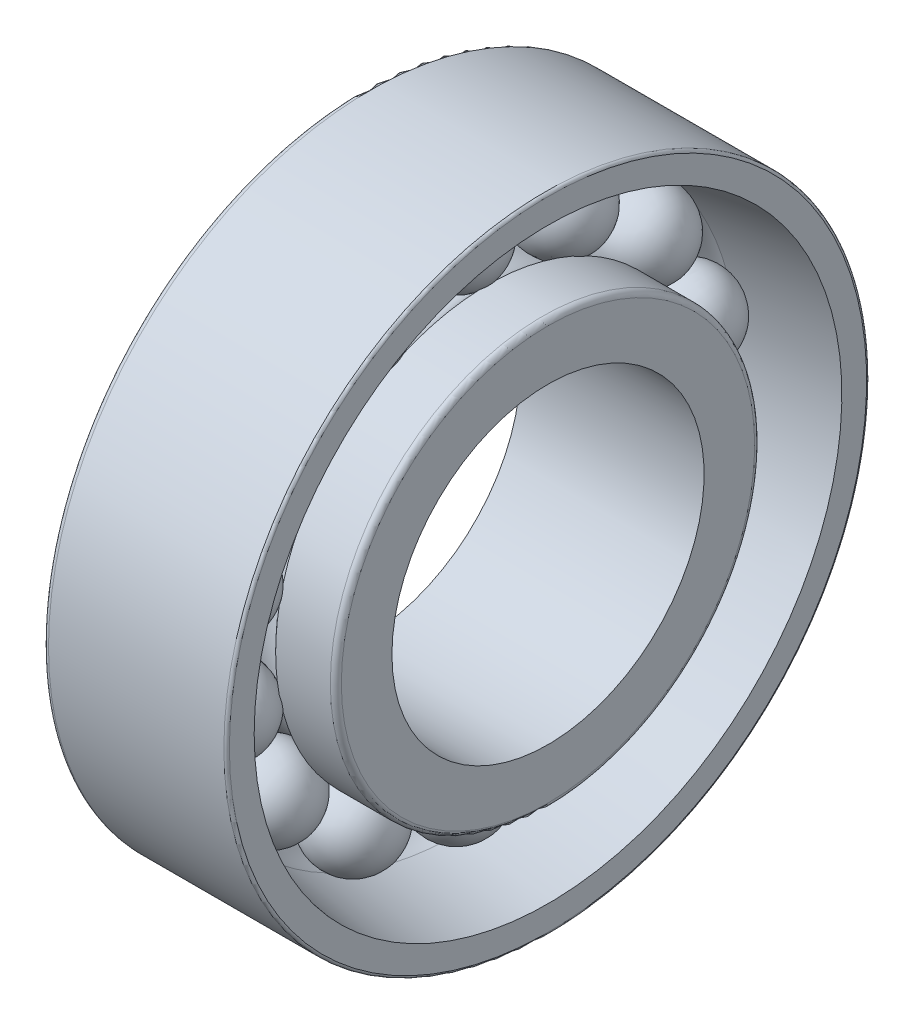
SolidWorks part; units mm, degrees
material "GCr15"
ref_plane "前视" through (0, 0, 0) normal (0, 0, 1) x (1, 0, 0)
ref_plane "上视" through (0, 0, 0) normal (0, 1, 0) x (1, 0, 0)
ref_plane "右视" through (0, 0, 0) normal (1, 0, 0) x (0, 0, -1)
sketch "尺寸草图" plane through (0, 0, 0) normal (0, 0, 1) x (1, 0, 0)
  line L0 (-3.205, -4.1476) -> (31.795, -4.1476)
  point P2 (13.795, -4.1476)
  point P3 (3.795, -4.1476)
  point P4 (0.7517, -4.1476)
  point P7 (31.645, -4.1476)
  point P8 (31.495, -4.1476)
  dimension "DD" = 35
  dimension "d" = 17
  dimension "B" = 10
  dimension "r1" = 0.15
  dimension "r" = 0.3
sketch "草图1" plane through (0, 0, 0) normal (0, 0, 1) x (1, 0, 0)
  line L0 (0, 0) -> (106.1418, 0) construction
  line L1 (0, 0) -> (0, 122.9209) construction
  line L2 (0, 17.5) -> (10, 17.5)
  line L3 (0, 8.5) -> (10, 8.5)
  line L4 (0, 17.5) -> (0, 8.5)
  line L5 (10, 17.5) -> (10, 11.5537)
  line L6 (10, 8.5) -> (10, 11.5537)
  line L7 (10, 11.5537) -> (0, 11.5537)
  line L9 (0, 13) -> (95.9613, 13) construction
  line L10 (5, 0) -> (5, 122.9209) construction
  line L11 (5, 15.25) -> (9, 15.25)
  line L12 (3.2764, 14.4463) -> (0, 14.4463)
  line L13 (9, 15.25) -> (9, 16)
  line L14 (9, 16) -> (10, 16)
  line L15 (5, 13) -> (3.2764, 14.4463) construction
  circle A0 centre (5, 13) radius 2.25
  dimension "D1" = 10
  dimension "D2" = 5
  dimension "D4" = 17
  dimension "D5" = 35
  dimension "D6" = 10
  dimension "D9" = 3
  dimension "D10" = 1
  dimension "D3" = 50
  dimension "D8" = 2.25
sketch "草图2" plane through (0, 0, 0) normal (0, 0, 1) x (1, 0, 0)
  line L0 (9, 15.25) -> (9, 16) construction
  line L1 (9, 16) -> (10, 16) construction
  line L2 (0, 17.5) -> (10, 17.5) construction
  line L3 (5, 15.25) -> (9, 15.25) construction
  line L4 (3.2764, 14.4463) -> (0, 14.4463) construction
  line L5 (0, 0) -> (106.1418, 0) construction
  line L6 (9, 15.25) -> (9, 16) construction
  line L7 (9, 16) -> (10, 16) construction
  line L8 (0, 17.5) -> (10, 17.5)
  line L9 (5, 15.25) -> (9, 15.25) construction
  line L10 (3.2764, 14.4463) -> (0, 14.4463)
  line L11 (0, 0) -> (106.1418, 0) construction
  line L12 (10, 17.5) -> (10, 11.5537) construction
  line L13 (0, 17.5) -> (0, 8.5) construction
  line L14 (10, 17.5) -> (10, 16)
  line L15 (0, 17.5) -> (0, 14.4463)
  line L16 (10, 16) -> (5, 15.25)
  circle A0 centre (5, 13) radius 2.25 construction
  arc A1 (5, 15.25) -> (3.2764, 14.4463) centre (5, 13) ccw
revolve "基体-旋转" add sketch "草图2" angle 360 about L11
sketch "草图3" plane through (0, 0, 0) normal (0, 0, 1) x (1, 0, 0)
  line L0 (0, 13) -> (95.9613, 13) construction
  line L1 (0, 13) -> (95.9613, 13) construction
  line L2 (7.3, 13) -> (2.7, 13)
  arc A0 (7.3, 13) -> (2.7, 13) centre (5, 13) ccw
  circle A1 centre (5, 13) radius 2.25
  arc A2 (7.25, 13) -> (2.75, 13) centre (5, 13) ccw construction
  dimension "D1" = 0
  dimension "D2" = 0.05
revolve "凸台-旋转1" add sketch "草图3" angle 360 about L1
sketch "草图4" plane through (0, 0, 0) normal (0, 0, 1) x (1, 0, 0)
  line L0 (10, 8.5) -> (10, 11.5537) construction
  line L1 (0, 17.5) -> (0, 8.5) construction
  line L2 (0, 8.5) -> (10, 8.5) construction
  line L3 (10, 11.5537) -> (0, 11.5537) construction
  line L4 (10, 8.5) -> (10, 11.5537)
  line L5 (3.2764, 11.5537) -> (0, 11.5537)
  line L6 (0, 8.5) -> (10, 8.5)
  line L7 (10, 11.5537) -> (6.7236, 11.5537)
  line L8 (0, 0) -> (106.1418, 0) construction
  line L9 (0, 0) -> (106.1418, 0) construction
  line L11 (0, 11.5537) -> (0, 8.5)
  circle A0 centre (5, 13) radius 2.25 construction
  arc A1 (3.2764, 11.5537) -> (6.7236, 11.5537) centre (5, 13) ccw
revolve "凸台-旋转2" add sketch "草图4" angle 360 about L9
fillet "圆角1" radius 0.15 1 edges at (10, 0, 17.5)
fillet "圆角2" radius 0.3 2 edges at (10, 0, 11.5537) (0, 0, 17.5)
pattern_circular "阵列(圆周)2" count 14 over 360 about axis through (0, 0, 0) along (1, 0, 0) of "凸台-旋转1"
equation "\"D5@草图1\" = \"DD@尺寸草图\""
equation "\"D6@草图1\" = \"B@尺寸草图\""
equation "\"D1@圆角2\" = \"r@尺寸草图\""
equation "\"D1@圆角1\" = \"r1@尺寸草图\""
equation "\"D4@草图1\" = \"d@尺寸草图\""
equation "\"D1@阵列(圆周)2\" =3.14* (  \"DD@尺寸草图\" + \"d@尺寸草图\" )  / 2/ (  ( \"DD@尺寸草图\" - \"d@尺寸草图\" )  / 3 ) "
equation "\"D1@草图1\" = \"D6@草图1\""
equation "\"D2@草图1\" = \"D1@草图1\" / 2"
equation "\"D9@草图1\" =   ( \"D5@草图1\" - \"D4@草图1\" )  /6"
equation "\"D8@草图1\" =  ( \"D5@草图1\" - \"D4@草图1\" )  / 8"
